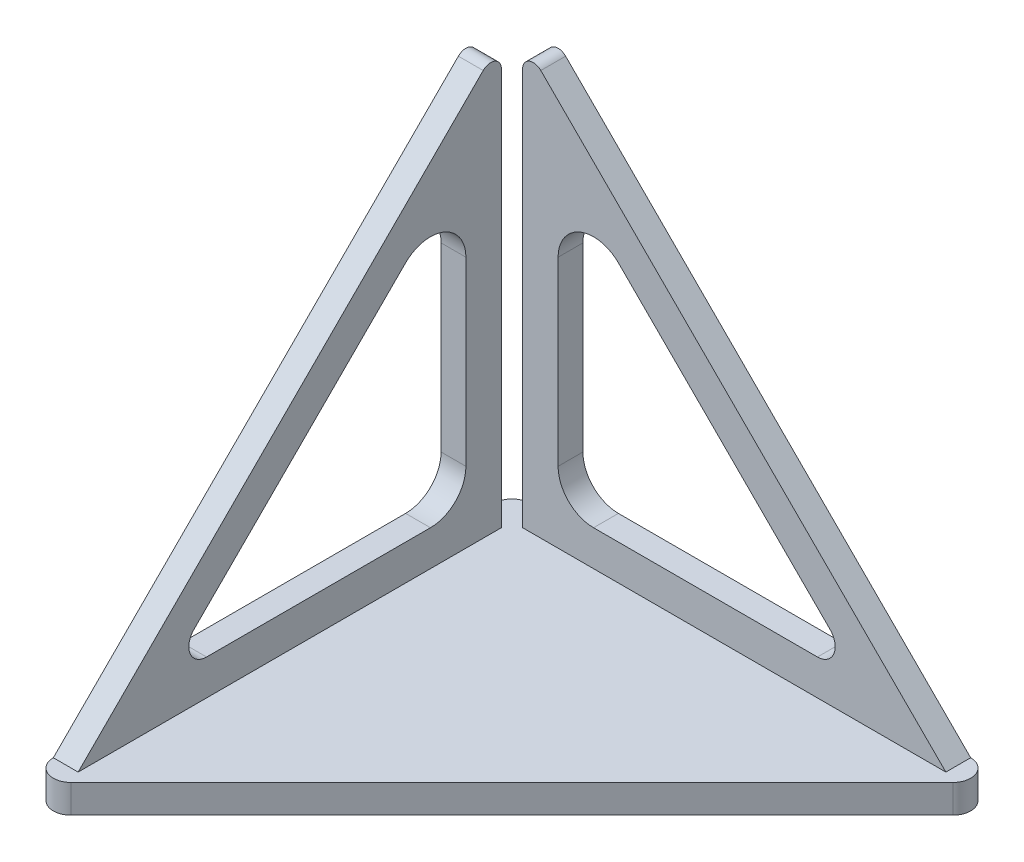
SolidWorks part; units mm, degrees
ref_plane "Front Plane" through (0, 0, 0) normal (0, 0, 1) x (1, 0, 0)
ref_plane "Top Plane" through (0, 0, 0) normal (0, 1, 0) x (1, 0, 0)
ref_plane "Right Plane" through (0, 0, 0) normal (1, 0, 0) x (0, 0, -1)
sketch "Sketch1" plane through (0, 0, 0) normal (0, 1, 0) x (1, 0, 0)
  line L0 (8.5355, -132.8858) -> (132.8858, -8.5355)
  line L1 (129.3503, 0) -> (5, 0)
  line L2 (0, -5) -> (0, -129.3503)
  line L3 (0, 0) -> (70.7107, -70.7107) construction
  arc A0 (5, 0) -> (0, -5) centre (5, -5) ccw
  arc A1 (132.8858, -8.5355) -> (129.3503, 0) centre (129.3503, -5) ccw
  arc A2 (8.5355, -132.8858) -> (0, -129.3503) centre (5, -129.3503) cw
  point P3 (70.7107, -70.7107)
  dimension "D2" = 5
  dimension "D1" = 100
extrude "Boss-Extrude1" add sketch "Sketch1" against normal blind 8
sketch "Sketch4" plane through (0, 0, 0) normal (0, 0, -1) x (-1, 0, 0)
  line L0 (-10, 0) -> (-10, 119.3503)
  line L1 (-10, 119.3503) -> (-129.3503, 0)
  line L2 (-129.3503, 0) -> (-10, 0)
  point P5 (0, 0)
  dimension "D1" = 45
  dimension "D2" = 5
sketch "Sketch5" plane through (0, 0, 0) normal (-1, 0, 0) x (0, 0, 1)
  line L0 (10, 0) -> (10, 119.3503)
  line L1 (10, 119.3503) -> (129.3503, 0)
  line L2 (129.3503, 0) -> (10, 0)
  point P5 (0, 0)
  dimension "D1" = 45
  dimension "D2" = 5
extrude "Extrude-Thin1" add sketch "Sketch4" against normal blind 7 thin contours L0 L1 L2 thin type one direction reverse wall 10
extrude "Extrude-Thin2" add sketch "Sketch5" against normal blind 7 thin contours L1 L2 L0
fillet "Fillet1" radius 10 4 edges at (3.5, 95.2082, 20) (3.5, 10, 20) (20, 95.2082, 3.5) (20, 10, 3.5)
fillet "Fillet2" radius 5 2 edges at (3.5, 10, 105.2082) (105.2082, 10, 3.5)
fillet "Fillet3" radius 3 2 edges at (10, 119.3503, 3.5) (3.5, 119.3503, 10)
